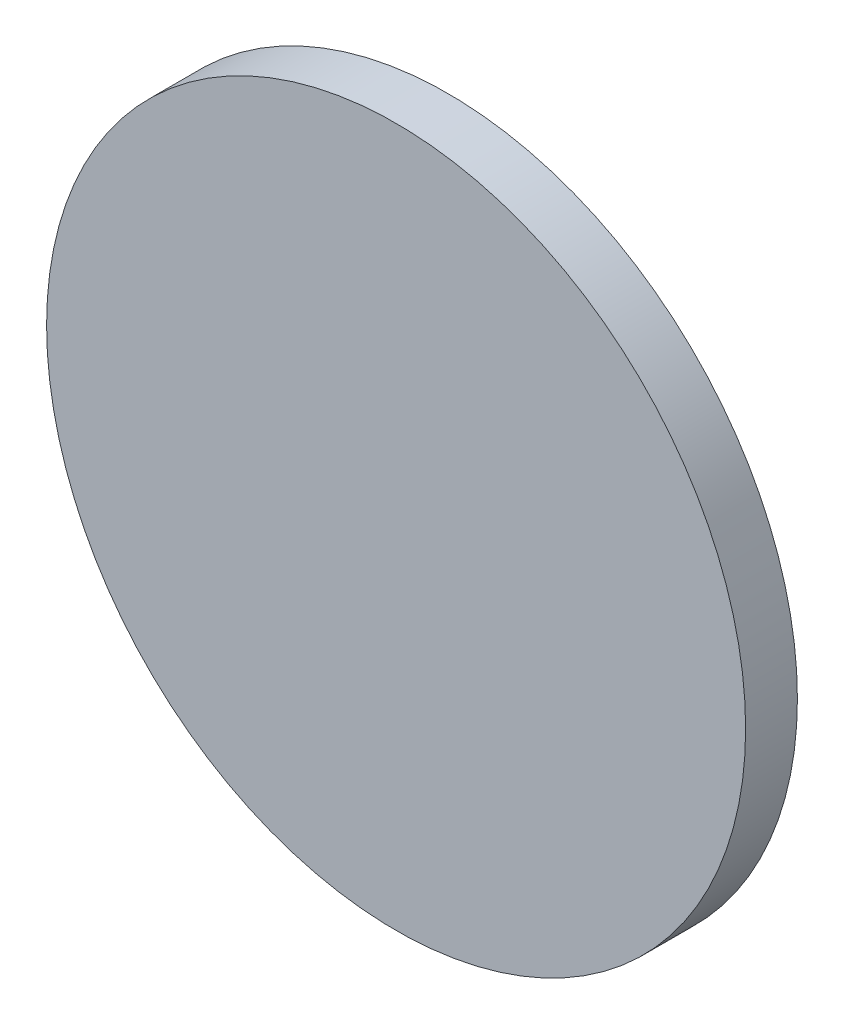
SolidWorks part; units mm, degrees
material "Acrylic (Medium-high impact)"
ref_plane "Front Plane" through (0, 0, 0) normal (0, 0, 1) x (1, 0, 0)
ref_plane "Top Plane" through (0, 0, 0) normal (0, 1, 0) x (1, 0, 0)
ref_plane "Right Plane" through (0, 0, 0) normal (1, 0, 0) x (0, 0, -1)
sketch "Sketch1" plane through (0, 0, 0) normal (0, 0, 1) x (1, 0, 0)
  circle A0 centre (0, 0) radius 5.4
  dimension "D1" = 10.8
extrude "Boss-Extrude1" add sketch "Sketch1" against normal blind 0.8 contours A0
sketch "Sketch2" [suppressed] plane through (0, 0, 0) normal (0, 0, -1) x (-1, 0, 0)
  circle A0 centre (0, 0) radius 1
  dimension "D1" = 2
split line "Split Line1" [suppressed]
